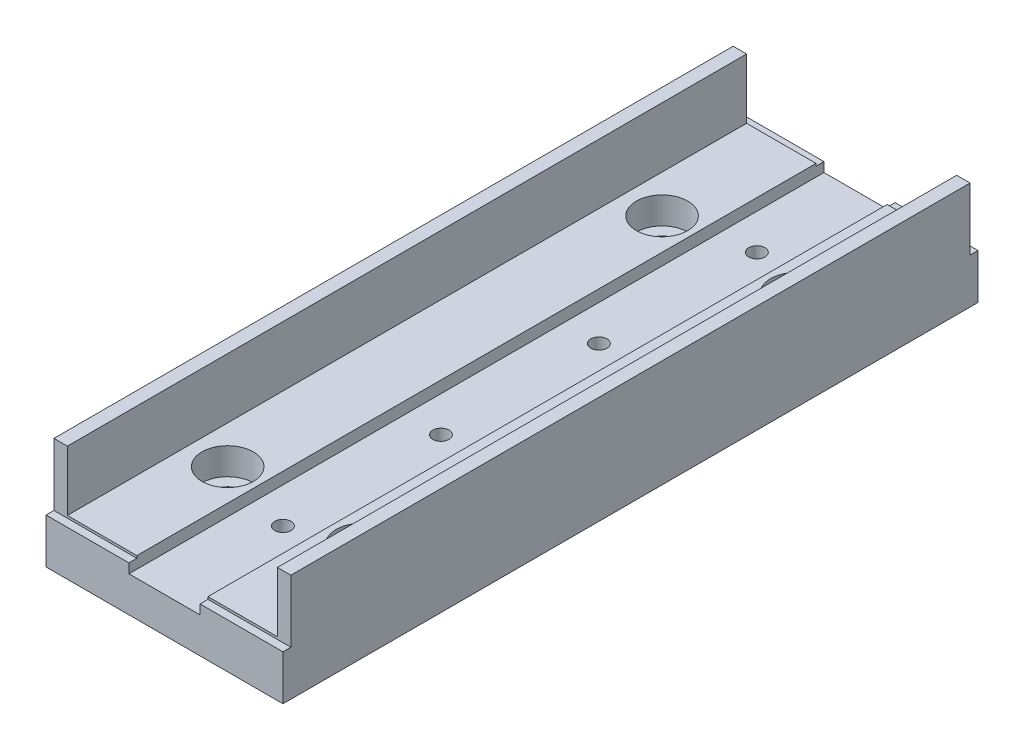
SolidWorks part; units mm, degrees
ref_plane "Спереди" through (0, 0, 0) normal (0, 0, 1) x (1, 0, 0)
ref_plane "Сверху" through (0, 0, 0) normal (0, 1, 0) x (1, 0, 0)
ref_plane "Справа" through (0, 0, 0) normal (1, 0, 0) x (0, 0, -1)
sketch "Эскиз1" plane through (0, 0, 0) normal (0, 0, 1) x (1, 0, 0)
  line L0 (0, 0) -> (0, 13.1204) construction
  line L1 (-15, -3) -> (15, -3)
  line L2 (-15, -3) -> (-15, 3)
  line L3 (-13.3, 3) -> (-4.5, 3)
  line L4 (15, -3) -> (15, 3)
  line L5 (-15, -3) -> (0, 0) construction
  line L6 (0, 0) -> (15, -3) construction
  line L8 (-15, 3) -> (-15, 10.6)
  line L9 (-15, 10.6) -> (-13.3, 10.6)
  line L10 (-13.3, 3) -> (-13.3, 10.6)
  line L11 (15, 10.6) -> (13.3, 10.6)
  line L12 (13.3, 3) -> (13.3, 10.6)
  line L13 (15, 3) -> (15, 10.6)
  line L14 (-4.5, 3) -> (-4.5, 1.5)
  line L15 (-4.5, 1.5) -> (4.5, 1.5)
  line L16 (4.5, 1.5) -> (4.5, 3)
  line L17 (4.5, 3) -> (13.3, 3)
  point P0 (0, 0)
  dimension "D1" = 30
  dimension "D2" = 6
  dimension "D3" = 7.6
  dimension "D4" = 1.7
  dimension "D5" = 9
  dimension "D6" = 1.5
extrude "Body" add sketch "Эскиз1" along normal blind 88
sketch "Эскиз2" plane through (0, 10.6, 0) normal (0, 1, 0) x (1, 0, 0)
  line L0 (15, -88) -> (15, 0) construction
  line L1 (-15, -88) -> (15, -88)
  line L2 (-15, -88) -> (-15, -87)
  line L3 (-15, -87) -> (15, -87)
  line L4 (15, -88) -> (15, -87)
  line L5 (-15, -44) -> (15, -44) construction
  line L6 (-15, -88) -> (-15, 0) construction
  line L7 (15, 0) -> (15, -1)
  line L8 (-15, -1) -> (15, -1)
  line L9 (-15, 0) -> (-15, -1)
  line L10 (-15, 0) -> (15, 0)
  dimension "D1" = 1
extrude "Cut1" cut sketch "Эскиз2" against normal offset from surface (7.9 mm away) 0.3 up to face at (-8.9, 3, 44) offset beyond the face yes
sketch "Эскиз3" plane through (0, 3, 0) normal (0, 1, 0) x (1, 0, 0)
  line L0 (0, 0) -> (0, -88) construction
  line L1 (4.5, -88) -> (-4.5, -88) construction
  line L2 (0, -44) -> (15, -44) construction
  line L3 (15, -87) -> (15, -1) construction
  point P3 (8.5, -16.5)
  point P6 (-8.5, -16.5)
  point P7 (8.5, -71.5)
  point P9 (-8.5, -71.5)
  dimension "D1" = 55
  dimension "D2" = 17
hole_wizard "Fixture M3" positions "Трехмерный эскиз1" profile "Эскиз4" counterbore size "M3" standard "ISO"
sketch3d "Трехмерный эскиз1"
  point P0 (-8.5, 3, 71.5)
  point P3 (8.5, 3, 71.5)
  point P6 (8.5, 3, 16.5)
  point P9 (-8.5, 3, 16.5)
sketch "Эскиз4" plane through (-8.5, 3, 71.5) normal (1, 0, 0) x (0, 0, 1)
  line L0 (0, 0) -> (0, 7.0215)
  line L1 (0, 7.0215) -> (1.7, 6)
  line L2 (1.7, 6) -> (1.7, 3.4)
  line L3 (1.7, 3.4) -> (3.25, 3.4)
  line L4 (3.25, 3.4) -> (3.25, 0)
  line L5 (3.25, 0) -> (0, 0)
  line L10 (0, 7.0215) -> (-1.7, 6) construction
  line L11 (0, -6.35) -> (0, 107.95) construction
  dimension "Диаметр отверстия" = 3.4
  dimension "Глубина отверстия" = 6
  dimension "Диаметр цековки" = 6.5
  dimension "Глубина цековки" = 3.4
  dimension "Угол заточки сверла" = 118
sketch "Эскиз6" plane through (0, 1.5, 0) normal (0, 1, 0) x (1, 0, 0)
  line L0 (0, 0) -> (0, -88) construction
  line L1 (4.5, -88) -> (-4.5, -88) construction
  point P0 (0, -73)
  dimension "D1" = 15
hole_wizard "Fixture M2" positions "Трехмерный эскиз2" profile "Эскиз7" tap size "M2.5" standard "ISO"
sketch3d "Трехмерный эскиз2"
  point P0 (0, 1.5, 73)
sketch "Эскиз7" plane through (0, 1.5, 73) normal (1, 0, 0) x (0, 0, 1)
  line L0 (0, 0) -> (0, 5.1159)
  line L1 (0, 5.1159) -> (1.025, 4.5)
  line L2 (1.025, 4.5) -> (1.025, 0)
  line L5 (1.025, 0) -> (0, 0)
  line L10 (0, 5.1159) -> (-1.025, 4.5) construction
  line L11 (0, -6.35) -> (0, 107.95) construction
  dimension "Диаметр сверла" = 2.05
  dimension "Глубина сверла" = 4.5
  dimension "Угол заточки сверла" = 118
cosmetic thread "Отверстие резьбы4" parameters "D1"=4.5, "D2"=2.5
pattern_linear "Линейный массив1" count 4 spacing 20 along (0, 0, -1) of "Fixture M2"
